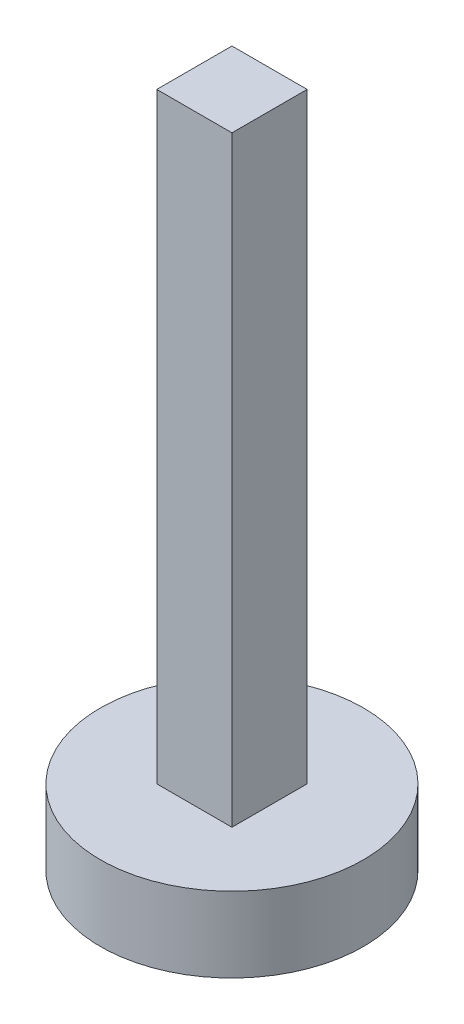
SolidWorks part; units mm, degrees
ref_plane "前视基准面" through (0, 0, 0) normal (0, 0, 1) x (1, 0, 0)
ref_plane "上视基准面" through (0, 0, 0) normal (0, 1, 0) x (1, 0, 0)
ref_plane "右视基准面" through (0, 0, 0) normal (1, 0, 0) x (0, 0, -1)
other "Configuration Table"
sketch "草图1" plane through (0, 0, 0) normal (0, 1, 0) x (1, 0, 0)
  line L1 (-5, -5) -> (5, -5)
  line L2 (-5, -5) -> (-5, 5)
  line L3 (-5, 5) -> (5, 5)
  line L4 (5, -5) -> (5, 5)
  line L5 (-5, -5) -> (5, 5) construction
  line L6 (-5, 5) -> (5, -5) construction
  point P0 (0, 0)
  dimension "D2" = 10
  dimension "D3" = 10
extrude "凸台-拉伸1" add sketch "草图1" along normal blind 80
sketch "草图2" plane through (0, 0, 0) normal (0, -1, 0) x (1, 0, 0)
  circle A0 centre (0, 0) radius 17.5
  point P2 (0, 0)
  point P3 (-2.3362, -1.8456)
  dimension "D1" = 35
extrude "凸台-拉伸2" add sketch "草图2" along normal blind 10
